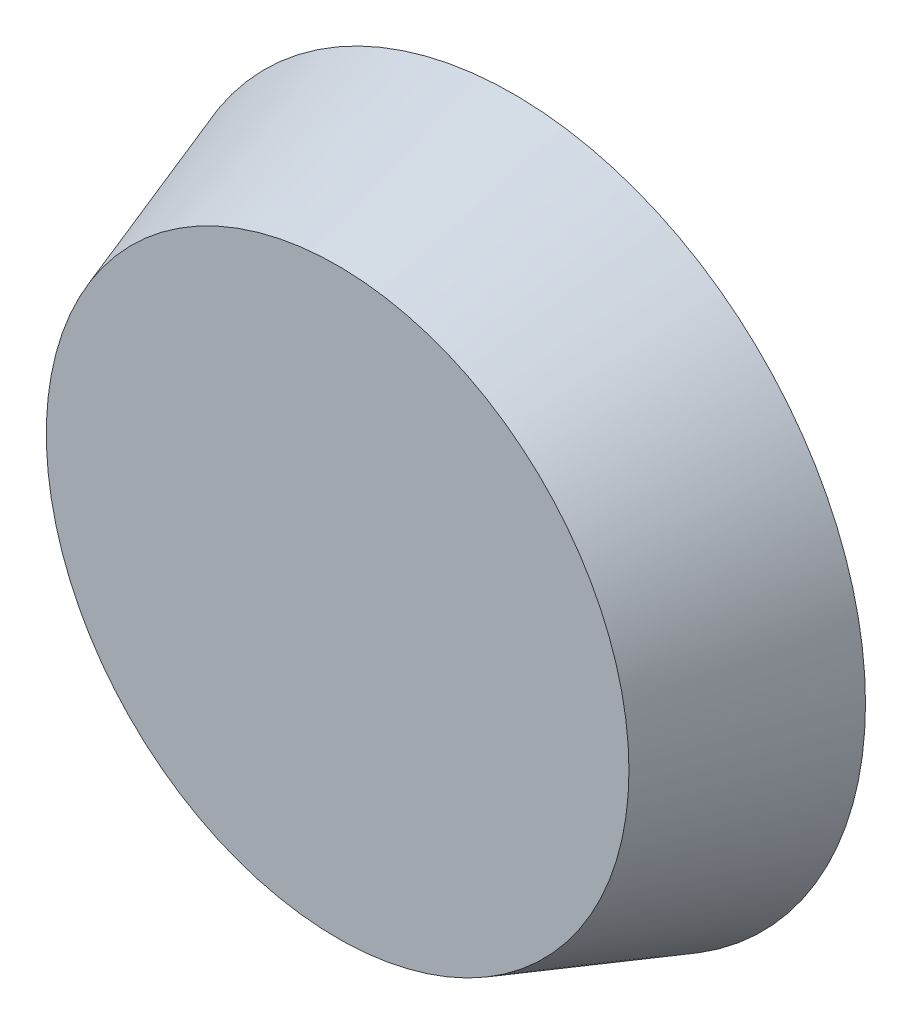
SolidWorks part; units mm, degrees
ref_plane "Ön Düzlem" through (0, 0, 0) normal (0, 0, 1) x (1, 0, 0)
ref_plane "Üst Düzlem" through (0, 0, 0) normal (0, 1, 0) x (1, 0, 0)
ref_plane "Sağ Düzlem" through (0, 0, 0) normal (1, 0, 0) x (0, 0, -1)
sketch "Çizim1" plane through (0, 0, 0) normal (0, 0, 1) x (1, 0, 0)
  circle A0 centre (0, 0) radius 1
  dimension "D1" = 2
extrude "Ekstrüzyon-İnce1" add sketch "Çizim1" along normal blind 1 draft 19 thin
sketch "Çizim2" plane through (0, 0, 1) normal (0, 0, 1) x (1, 0, 0)
  circle A0 centre (0, 0) radius 1.6557
extrude "Yükseklik-Ekstrüzyon1" add sketch "Çizim2" against normal blind 0.1
